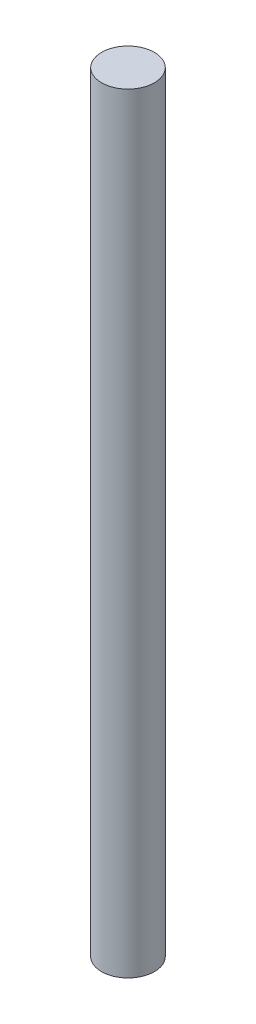
SolidWorks part; units mm, degrees
ref_plane "Alzado" through (0, 0, 0) normal (0, 0, 1) x (1, 0, 0)
ref_plane "Planta" through (0, 0, 0) normal (0, 1, 0) x (1, 0, 0)
ref_plane "Vista lateral" through (0, 0, 0) normal (1, 0, 0) x (0, 0, -1)
sketch "Croquis1" plane through (0, 0, 0) normal (0, 1, 0) x (1, 0, 0)
  circle A0 centre (0, 0) radius 6
  dimension "D1" = 12
extrude "Saliente-Extruir1" add sketch "Croquis1" along normal mid plane 175
